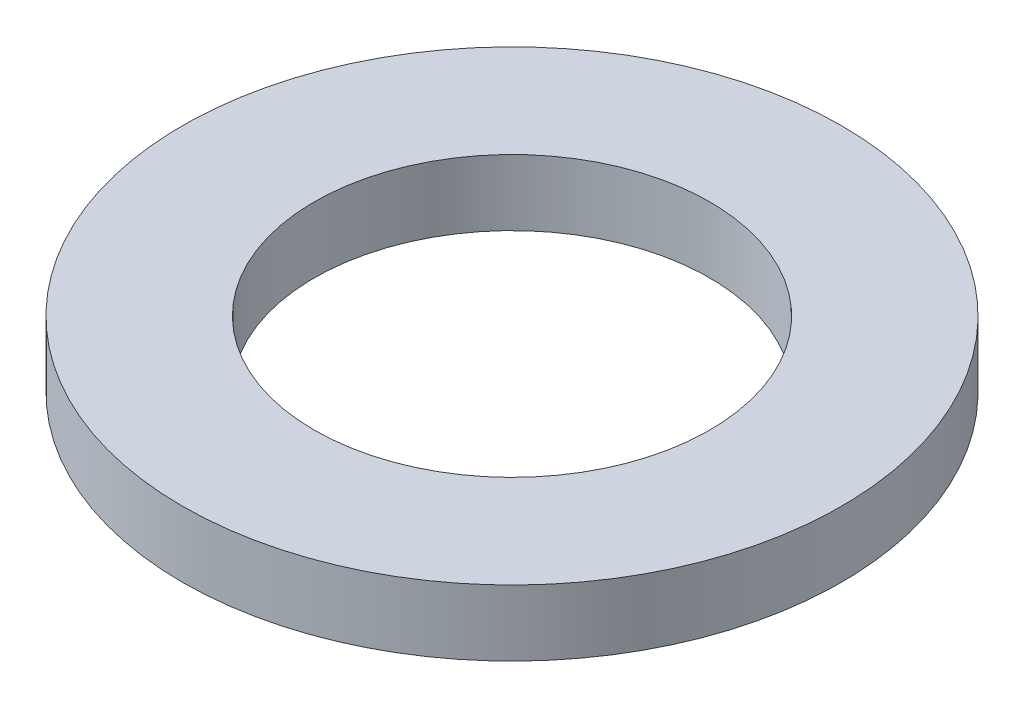
SolidWorks part; units mm, degrees
ref_plane "Front Plane" through (0, 0, 0) normal (0, 0, 1) x (1, 0, 0)
ref_plane "Top Plane" through (0, 0, 0) normal (0, 1, 0) x (1, 0, 0)
ref_plane "Right Plane" through (0, 0, 0) normal (1, 0, 0) x (0, 0, -1)
sketch "Sketch1" plane through (0, 0, 0) normal (0, 1, 0) x (1, 0, 0)
  circle A0 centre (0, 0) radius 10
  circle A1 centre (0, 0) radius 6
  dimension "D1" = 20
  dimension "D2" = 12
extrude "Boss-Extrude1" add sketch "Sketch1" along normal blind 2
